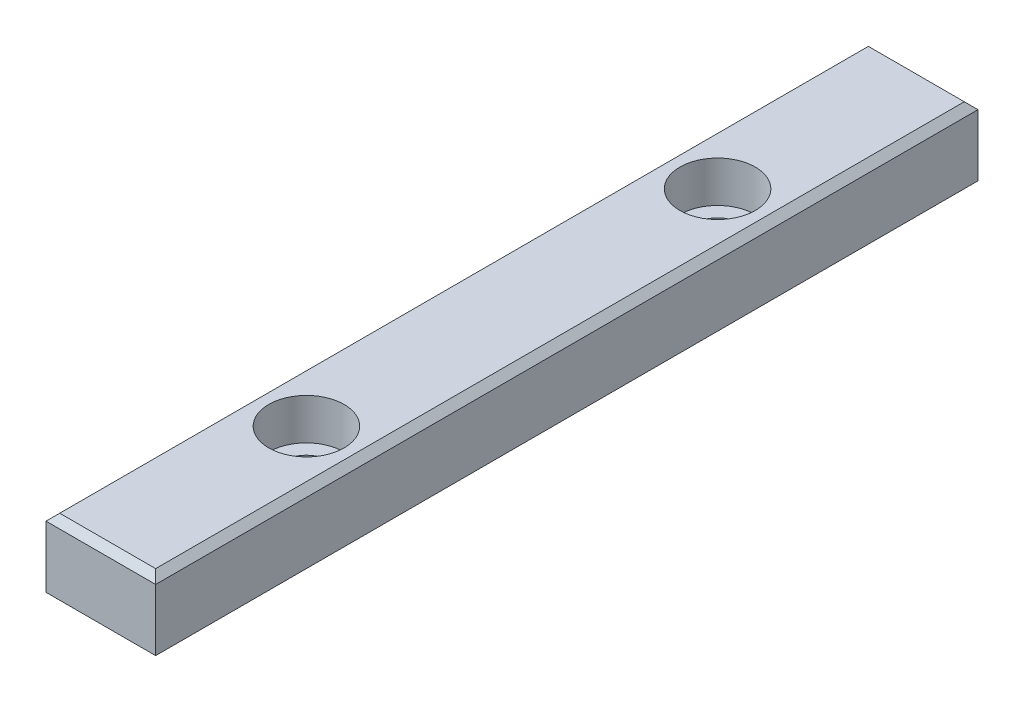
SolidWorks part; units mm, degrees
ref_plane "Спереди" through (0, 0, 0) normal (0, 0, 1) x (1, 0, 0)
ref_plane "Сверху" through (0, 0, 0) normal (0, 1, 0) x (1, 0, 0)
ref_plane "Справа" through (0, 0, 0) normal (1, 0, 0) x (0, 0, -1)
sketch "Эскиз1" plane through (0, 0, 0) normal (0, 1, 0) x (1, 0, 0)
  line L0 (-8, 60) -> (8, -60) construction
  line L1 (8, -60) -> (-8, -60)
  line L2 (8, -60) -> (8, 60)
  line L3 (8, 60) -> (-8, 60)
  line L4 (-8, -60) -> (-8, 60)
  dimension "D1" = 120
  dimension "D2" = 16
extrude "Бобышка-Вытянуть1" add sketch "Эскиз1" against normal blind 10
chamfer "Фаска1" distance 1 angle 45 4 edges at (8, 0, 0) (0, 0, -60) (-8, 0, 0) (0, 0, 60)
hole_wizard "Цековка для винта с внутренним шестигранником M61" positions "Эскиз3" profile "Эскиз2" counterbore size "M6" standard "ISO" end condition through all
sketch "Эскиз3" plane through (0, 0, 0) normal (0, 1, 0) x (-1, 0, 0)
  line L0 (-8, 60) -> (8, 60) construction
  point P0 (0, 30)
  point P1 (0, -30)
  dimension "D1" = 60
  dimension "D2" = 30
sketch "Эскиз2" plane through (0, 0, 30) normal (1, 0, 0) x (0, 0, 1)
  line L0 (0, 0) -> (0, 10)
  line L1 (0, 10) -> (3.3, 10)
  line L3 (3.3, 10) -> (3.3, 6)
  line L4 (3.3, 6) -> (5.5, 6)
  line L5 (5.5, 6) -> (5.5, 0)
  line L7 (5.5, 0) -> (0, 0)
  line L11 (0, -6.35) -> (0, 107.95) construction
  dimension "Диаметр сквозного отверстия" = 6.6
  dimension "Глубина сквозного отверстия" = 10
  dimension "Диаметр цековки" = 11
  dimension "Глубина цековки" = 6
ref_plane "face_for_mating" through (0, 0, 0) normal (0, 1, 0) x (1, 0, 0)
ref_plane "face_for_horizont" through (0, -10, 0) normal (0, -1, 0) x (-1, 0, 0)
equation "\"Length\"=120"
equation "\"D\"=14"
equation "\"D1@Эскиз1\" = \"Length\""
equation "\"D2@Эскиз3\" = \"D1@Эскиз1\"/4"
equation "\"D1@Эскиз3\" = \"D1@Эскиз1\"/2"
